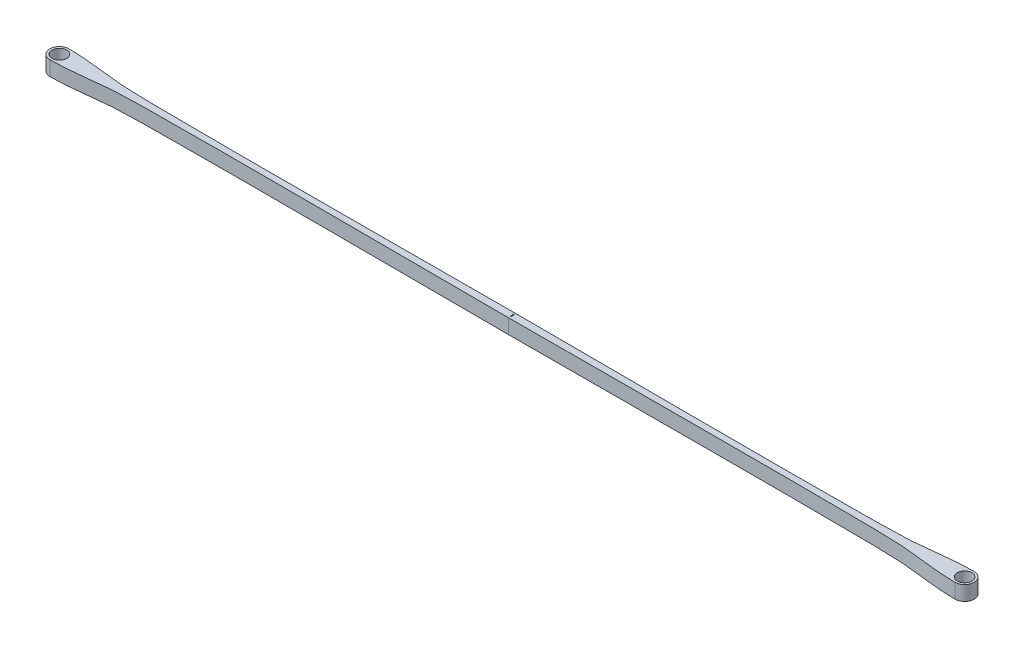
SolidWorks part; units mm, degrees
ref_plane "Front Plane" through (0, 0, 0) normal (0, 0, 1) x (1, 0, 0)
ref_plane "Top Plane" through (0, 0, 0) normal (0, 1, 0) x (1, 0, 0)
ref_plane "Right Plane" through (0, 0, 0) normal (1, 0, 0) x (0, 0, -1)
sketch "Sketch2" plane through (0, 0, 0) normal (0, 1, 0) x (1, 0, 0)
  line L1 (-1.1, 0) -> (1.1, 0) construction
  line L2 (61.9, 0.5) -> (61.9, -0.5)
  circle A0 centre (0, 0) radius 1.3
  spline S0 degree 3 poles (0, 1.3) (2.1583, 1.3) (7.6059, 0.5483) (11.0616, 0.324) (61.9, 0.5) knots 0 0 0 0 0.427834 1 1 1 1
  spline S1 degree 3 poles (0, -1.3) (2.1583, -1.3) (7.6059, -0.5483) (11.0616, -0.324) (61.9, -0.5) knots 0 0 0 0 0.427834 1 1 1 1
  dimension "D1" = 61.9
  dimension "D5" = 2.6
  dimension "D4" = 7.1253
  dimension "D6" = 15.0773
  dimension "D2" = 7.1943
  dimension "D3" = 1.364
  dimension "D7" = 1
extrude "Boss-Extrude1" add sketch "Sketch2" along normal blind 2 contours A0 S1 L2 S0
sketch "Sketch3" plane through (0, 2, 0) normal (0, 1, 0) x (1, 0, 0)
  circle A0 centre (0, 0) radius 1
  dimension "D1" = 2
extrude "Cut-Extrude1" cut sketch "Sketch3" against normal through all
ref_plane "Plane1" through (61.9, 0, 0) normal (1, 0, 0) x (0, 0, -1)
mirror "Mirror1" about plane through (61.9, 0, 0) normal (1, 0, 0) of "Boss-Extrude1", "Cut-Extrude1"
sketch "Sketch4" plane through (0, 2, 0) normal (0, 1, 0) x (1, 0, 0)
  line L0 (61.85, -0.2) -> (61.95, 0.3) construction
  line L1 (61.85, -0.2) -> (61.95, -0.2)
  line L2 (61.85, -0.2) -> (61.85, 0.3)
  line L3 (61.85, 0.3) -> (61.95, 0.3)
  line L4 (61.95, -0.2) -> (61.95, 0.3)
  line L5 (61.9, -1.1) -> (61.9, 1.1) construction
  point P4 (61.9, 0.05)
  dimension "D1" = 0.5
  dimension "D2" = 0.1
  dimension "D3" = 1.1
extrude "Cut-Extrude2" cut sketch "Sketch4" against normal blind 0.5
